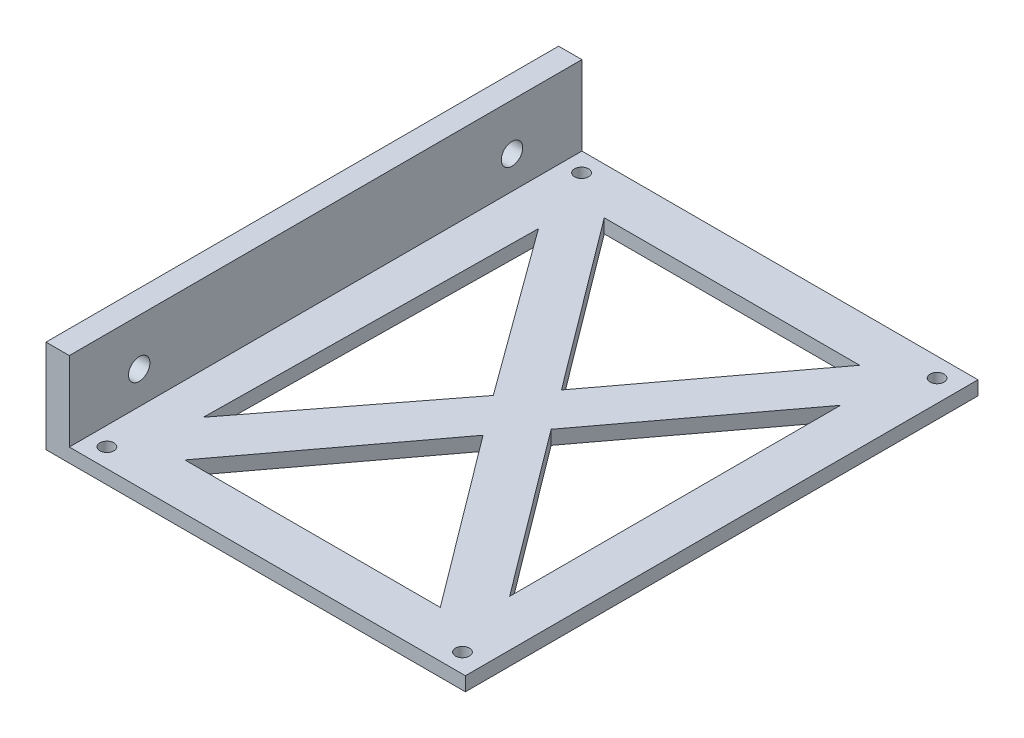
SolidWorks part; units mm, degrees
ref_plane "Front Plane" through (0, 0, 0) normal (0, 0, 1) x (1, 0, 0)
ref_plane "Top Plane" through (0, 0, 0) normal (0, 1, 0) x (1, 0, 0)
ref_plane "Right Plane" through (0, 0, 0) normal (1, 0, 0) x (0, 0, -1)
sketch "Sketch2" plane through (0, 0, 0) normal (1, 0, 0) x (0, 0, -1)
  line L1 (-55, -10) -> (55, -10)
  line L2 (-55, -10) -> (-55, 10)
  line L3 (-55, 10) -> (55, 10)
  line L4 (55, -10) -> (55, 10)
  line L5 (-55, -10) -> (55, 10) construction
  line L6 (-55, 10) -> (55, -10) construction
  point P0 (0, 0)
  dimension "D1" = 20
  dimension "D2" = 110
extrude "Boss-Extrude1" add sketch "Sketch2" along normal blind 5
sketch "Sketch3" plane through (0, -10, 0) normal (0, 1, 0) x (1, 0, 0)
  line L0 (5, -55) -> (0, -55) construction
  line L1 (5, 55) -> (90, 55)
  line L2 (5, 55) -> (5, -55)
  line L3 (5, -55) -> (90, -55)
  line L4 (90, 55) -> (90, -55)
  dimension "D1" = 85
extrude "Boss-Extrude2" add sketch "Sketch3" along normal blind 3
sketch "Sketch4" plane through (0, 0, 0) normal (1, 0, 0) x (0, 0, -1)
  line L0 (55, 0) -> (-55, 0) construction
  line L1 (55, -10) -> (55, 10) construction
  line L2 (-55, 10) -> (-55, -10) construction
  circle A0 centre (40, 0) radius 2.3
  circle A1 centre (-40, 0) radius 2.3
  dimension "D1" = 4.6
  dimension "D2" = 15
  dimension "D3" = 15
extrude "Cut-Extrude2" cut sketch "Sketch4" along normal blind 10
sketch "Sketch5" plane through (0, -10, 0) normal (0, -1, 0) x (1, 0, 0)
  line L0 (90, 55) -> (0, 55) construction
  line L1 (85.3, -50.925) -> (9, -50.925) construction
  line L2 (85.3, -50.925) -> (85.3, 50.925) construction
  line L3 (85.3, 50.925) -> (9, 50.925) construction
  line L4 (9, -50.925) -> (9, 50.925) construction
  circle A0 centre (9, 50.925) radius 1.4988
  circle A1 centre (85.3, 50.925) radius 1.4988
  circle A2 centre (85.3, -50.925) radius 1.4988
  circle A3 centre (9, -50.925) radius 1.4988
  dimension "D5" = 2.9976
  dimension "D1" = 9
  dimension "D2" = 76.3
  dimension "D3" = 4.075
  dimension "D4" = 101.85
extrude "Cut-Extrude3" cut sketch "Sketch5" against normal blind 10
sketch "Sketch6" plane through (0, -7, 0) normal (0, 1, 0) x (1, 0, 0)
  line L0 (9, 50.925) -> (85.3, -50.925) construction
  line L1 (85.3, 50.925) -> (9, -50.925) construction
  line L2 (80, 35.5108) -> (53.3974, 0)
  line L3 (53.3974, 0) -> (80, -35.5108)
  line L4 (80, -35.5108) -> (80, 35.5108)
  line L5 (90, -55) -> (90, 55) construction
  line L6 (46.8, -55) -> (47.5, 55) construction
  line L7 (90, 55) -> (5, 55) construction
  line L8 (40.9031, 0.0795) -> (13.8507, -35.0898)
  line L9 (14.7546, 35.926) -> (40.9031, 0.0795)
  line L10 (13.8507, -35.0898) -> (14.7546, 35.926)
  line L11 (19.7931, 45) -> (47.2035, 8.4109)
  line L12 (47.2035, 8.4109) -> (74.6139, 45)
  line L13 (74.6139, 45) -> (19.7931, 45)
  line L14 (5, 0) -> (90, 0) construction
  line L15 (5, 55) -> (5, -55) construction
  line L16 (47.2035, -8.4109) -> (74.6139, -45)
  line L17 (19.7931, -45) -> (47.2035, -8.4109)
  line L18 (74.6139, -45) -> (19.7931, -45)
  point P16 (47.15, 0)
  point P19 (47.15, 0)
  dimension "D1" = 10
  dimension "D2" = 10
  dimension "D3" = 5
  dimension "D4" = 5
extrude "Cut-Extrude4" cut sketch "Sketch6" against normal blind 10
